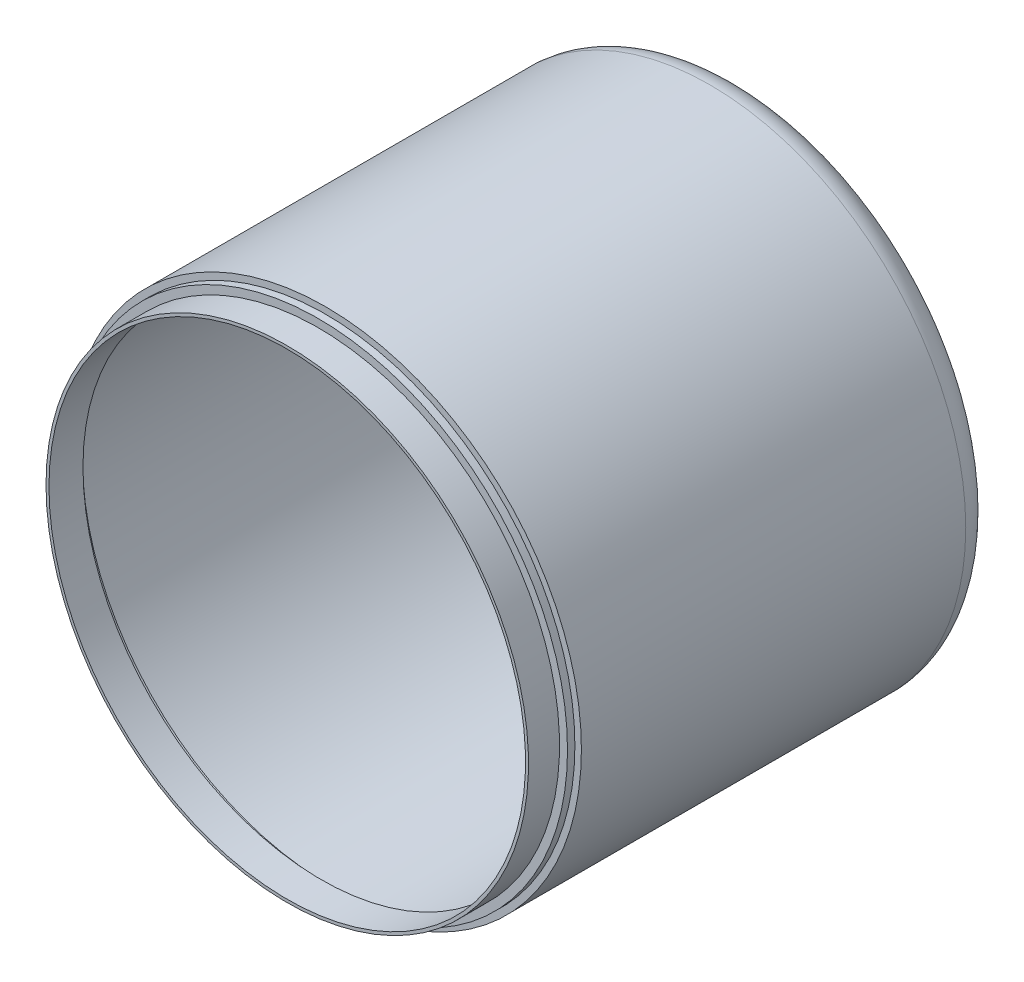
SolidWorks part; units mm, degrees
ref_plane "Piano frontale" through (0, 0, 0) normal (0, 0, 1) x (1, 0, 0)
ref_plane "Piano superiore" through (0, 0, 0) normal (0, 1, 0) x (1, 0, 0)
ref_plane "Piano destro" through (0, 0, 0) normal (1, 0, 0) x (0, 0, -1)
sketch "Schizzo1" plane through (0, 0, 0) normal (0, 0, 1) x (1, 0, 0)
  circle A0 centre (0, 0) radius 70
  dimension "D1" = 140
extrude "Estrusione-Estrusione1" add sketch "Schizzo1" along normal blind 2.2
sketch "Schizzo2" plane through (0, 0, 2.2) normal (0, 0, 1) x (1, 0, 0)
  circle A0 centre (0, 0) radius 86.5
  dimension "D1" = 173
extrude "Estrusione-Estrusione2" add sketch "Schizzo2" along normal blind 140
sketch "Schizzo3" plane through (0, 0, 142.2) normal (0, 0, 1) x (1, 0, 0)
  circle A0 centre (0, 0) radius 84.3
  circle A1 centre (0, 0) radius 86.5 construction
  dimension "D1" = 2.2
extrude "Estrusione-Estrusione3" add sketch "Schizzo3" along normal blind 2.5
sketch "Schizzo4" plane through (0, 0, 144.7) normal (0, 0, 1) x (1, 0, 0)
  circle A0 centre (0, 0) radius 81.6
  circle A1 centre (0, 0) radius 86.5 construction
  dimension "D1" = 4.9
extrude "Estrusione-Estrusione4" add sketch "Schizzo4" along normal blind 10.5
shell "Svuota1" thickness 1
fillet "Raccordo1" radius 10 2 edges at (85.5, 0, 3.2) (86.5, 0, 2.2)
